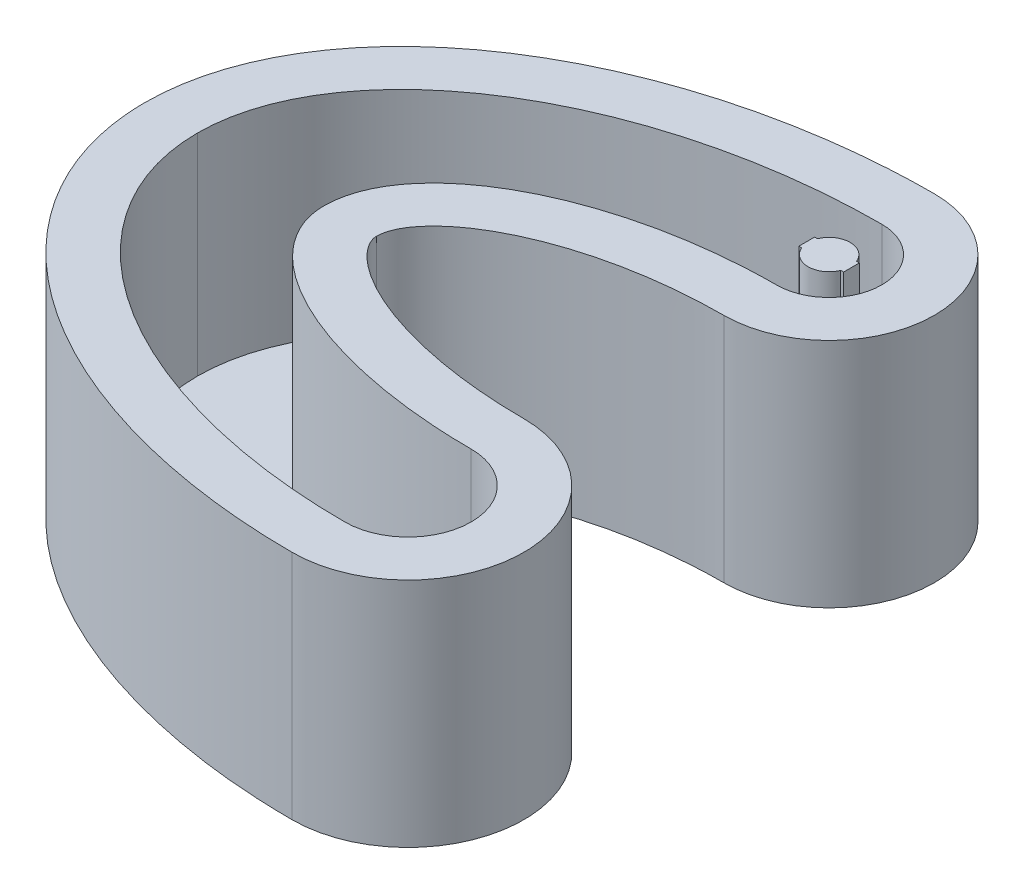
SolidWorks part; units mm, degrees
ref_plane "Front Plane" through (0, 0, 0) normal (0, 0, 1) x (1, 0, 0)
ref_plane "Top Plane" through (0, 0, 0) normal (0, 1, 0) x (1, 0, 0)
ref_plane "Right Plane" through (0, 0, 0) normal (1, 0, 0) x (0, 0, -1)
sketch "Sketch1" plane through (0, 0, 0) normal (0, 1, 0) x (1, 0, 0)
  line L0 (0, 0) -> (20, 0) construction
  line L1 (20, 0) -> (20, 25) construction
  line L2 (0, 0) -> (-20, 0) construction
  line L3 (20, 20) -> (25, 20) construction
  line L4 (17.875, 19.25) -> (22.125, 19.25)
  line L5 (17.875, 19.25) -> (17.875, 20.75)
  line L6 (17.875, 20.75) -> (22.125, 20.75)
  line L7 (22.125, 19.25) -> (22.125, 20.75)
  line L8 (17.875, 19.25) -> (22.125, 20.75) construction
  line L9 (17.875, 20.75) -> (22.125, 19.25) construction
  line L10 (25, 20) -> (25, -19) construction
  line L11 (25, -19) -> (19, -19) construction
  line L12 (19, -25) -> (19, 0) construction
  circle A2 centre (20, 20) radius 2
  arc A3 (20, 25) -> (20, 15) centre (20, 20) cw
  arc A4 (19, -25) -> (19, -13) centre (19, -19) ccw
  arc A5 (19, -35.1994) -> (19, 35.1994) centre (0, 0) ccw
  ellipse E0 centre (20, 0) end of major axis (-20, 0) minor radius 25 (-20, 0) -> (20, 25) cw
  ellipse E1 centre (20, 0) end of major axis (-8, 0) minor radius 15 (-8, 0) -> (20, 15) cw
  ellipse E2 centre (19, 0) end of major axis (46, 0) minor radius 13 (-8, 0) -> (19, -13) ccw
  ellipse E3 centre (19, 0) end of major axis (58, 0) minor radius 25 (-20, 0) -> (19, -25) ccw
  ellipse E4 centre (19, 0) end of major axis (-31, 0) minor radius 35.1994 (19, 35.1994) -> (19, -35.1994) ccw
  dimension "D3" = 5
  dimension "D7" = 4
  dimension "D9" = 39
  dimension "D11" = 6
  dimension "D13" = 80
  dimension "D1" = 20
  dimension "D2" = 25
  dimension "D4" = 20
  dimension "D5" = 12
  dimension "D6" = 4.25
  dimension "D8" = 1.5
  dimension "D10" = 6
  dimension "D12" = 19
  dimension "D14" = 50
  dimension "D15" = 35.1994
extrude "Boss-Extrude1" add sketch "Sketch1" along normal blind 20 contours A5 E4 E3 E0 A3 E1 E2 A4 | L6 L7 L4 L5 | A2
fillet "Fillet1" radius 20 2 edges at (19, 10, 35.1994) (19, 10, -35.1994)
sketch "Sketch7" plane through (0, 20, 0) normal (0, 1, 0) x (1, 0, 0)
  arc A7 (19, -30) -> (19, -8) centre (19, -19) ccw
  arc A8 (20, 10) -> (20, 30) centre (20, 20) ccw
  arc A9 (19, -30) -> (19, -8) centre (19, -19) ccw
  arc A10 (20, 10) -> (20, 30) centre (20, 20) ccw
  arc A12 (26.7157, -29.7703) -> (26.7157, 29.7703) centre (0, 0) ccw
  arc A13 (26.7157, 29.7703) -> (11.1268, 34.7603) centre (13.3579, 14.8851) ccw
  arc A14 (11.1268, -34.7603) -> (26.7157, -29.7703) centre (13.3579, -14.8851) ccw
  arc A15 (26.7157, -29.7703) -> (26.7157, 29.7703) centre (0, 0) ccw
  arc A16 (26.7157, 29.7703) -> (11.1268, 34.7603) centre (13.3579, 14.8851) ccw
  arc A17 (11.1268, -34.7603) -> (26.7157, -29.7703) centre (13.3579, -14.8851) ccw
  ellipse E6 centre (19, 0) end of major axis (-31, 0) minor radius 35.1994 (11.1268, 34.7603) -> (11.1268, -34.7603) ccw
  ellipse E7 centre (19, 0) end of major axis (-31, 0) minor radius 35.1994 (11.1268, 34.7603) -> (11.1268, -34.7603) ccw
  spline S0 degree 3 poles (2881.2153, 728.2994) (360.2182, 219.2635) (-38.0983, 72.6493) (-24.5732, -4.2682) (-24.4416, -4.8659) (-24.1276, -6.0526) (-23.9448, -6.6428) (-23.323, -8.3927) (-22.8187, -9.512) (-21.9426, -11.1279) (-21.6306, -11.656) (-20.9682, -12.692) (-20.6169, -13.2012) (-19.514, -14.6904) (-18.7208, -15.6237) (-17.0353, -17.3886) (-16.1429, -18.2201) (-14.738, -19.3991) (-14.2585, -19.7807) (-13.2784, -20.522) (-12.7764, -20.8826) (-11.2531, -21.9238) (-10.2126, -22.5659) (-7.0256, -24.356) (-4.8141, -25.3689) (-1.3874, -26.6604) (-0.2252, -27.053) (2.1282, -27.7628) (3.3107, -28.0776) (6.8745, -28.9108) (9.2719, -29.3188) (202.1373, -51.0483) (515.5099, 770.5689) (1003.1891, 2787.6642) knots -3.898537 -3.898537 -3.898537 -3.898537 0.0625 0.0625 0.09375 0.09375 0.125 0.125 0.1875 0.1875 0.21875 0.21875 0.25 0.25 0.3125 0.3125 0.375 0.375 0.40625 0.40625 0.4375 0.4375 0.5 0.5 0.625 0.625 0.6875 0.6875 0.75 0.75 0.875 0.875 10.723804 10.723804 10.723804 10.723804 only from (-25, 0) to (19, -30)
  spline S1 degree 3 poles (235.1817, -2911.03) (746.1862, 1589.4437) (242.5983, -35.9676) (10.9013, -7.3829) (8.9128, -7.0104) (5.9711, -6.2029) (4.9975, -5.8919) (3.0689, -5.1577) (2.1265, -4.7402) (0.7644, -4.0041) (0.322, -3.7419) (-0.5322, -3.1734) (-0.9444, -2.8676) (-1.7237, -2.191) (-2.0913, -1.8221) (-2.557, -1.1984) (-2.6958, -0.9817) (-2.8605, -0.6338) (-2.9082, -0.5139) (-5.5147, 8.8205) (66.4763, 33.2928) (2994.2774, -60.3933) knots -28.329853 -28.329853 -28.329853 -28.329853 0.25 0.25 0.5 0.5 0.625 0.625 0.75 0.75 0.8125 0.8125 0.875 0.875 0.9375 0.9375 0.96875 0.96875 0.984375 0.984375 2.122582 2.122582 2.122582 2.122582 only from (19, -8) to (-3, 0)
  spline S2 degree 3 poles (2931.8932, -616.5418) (131.158, -62.9524) (-7.7376, -17.3433) (-2.8149, 1.1048) (-2.7097, 1.3711) (-2.4613, 1.8742) (-2.3172, 2.1142) (-1.9996, 2.5771) (-1.8252, 2.8008) (-1.2763, 3.4396) (-0.8748, 3.8267) (-0.0246, 4.5495) (0.4268, 4.8859) (1.8219, 5.8238) (2.7986, 6.3525) (4.8131, 7.2837) (5.8526, 7.6849) (7.9772, 8.3835) (9.0481, 8.6761) (11.204, 9.1688) (12.2889, 9.3688) (229.0024, 40.9052) (685.3544, -1516.1991) (232.5259, 2926.0273) knots -2.063092 -2.063092 -2.063092 -2.063092 0.03125 0.03125 0.0625 0.0625 0.09375 0.09375 0.125 0.125 0.1875 0.1875 0.25 0.25 0.375 0.375 0.5 0.5 0.625 0.625 0.75 0.75 25.450462 25.450462 25.450462 25.450462 only from (-3, 0) to (20, 10)
  spline S3 degree 3 poles (1038.1549, -2775.3435) (507.3026, -688.6174) (197.7056, 49.7754) (10.1372, 29.3319) (7.7096, 28.9323) (4.1036, 28.118) (2.9075, 27.8105) (1.1229, 27.2911) (0.5296, 27.1083) (-0.6536, 26.7222) (-1.2446, 26.5186) (-4.1751, 25.4526) (-6.4419, 24.4488) (-9.7053, 22.677) (-10.7701, 22.0418) (-12.8476, 20.6697) (-13.8637, 19.9296) (-15.7971, 18.3618) (-16.7186, 17.532) (-18.46, 15.7697) (-19.2801, 14.8373) (-20.4214, 13.3486) (-20.7875, 12.8362) (-21.4769, 11.7945) (-21.8016, 11.2635) (-22.7132, 9.6392) (-23.238, 8.5145) (-23.8859, 6.7573) (-24.0792, 6.157) (-24.4112, 4.9479) (-24.5502, 4.3393) (-38.9862, -74.8555) (393.3239, -220.9265) (2892.8263, -679.3616) knots -9.322522 -9.322522 -9.322522 -9.322522 0.125 0.125 0.25 0.25 0.3125 0.3125 0.34375 0.34375 0.375 0.375 0.5 0.5 0.5625 0.5625 0.625 0.625 0.6875 0.6875 0.75 0.75 0.78125 0.78125 0.8125 0.8125 0.875 0.875 0.90625 0.90625 0.9375 0.9375 4.945268 4.945268 4.945268 4.945268 only from (20, 30) to (-25, 0)
  spline S4 degree 3 poles (-25, 0) (-25, -1.2403) (-24.8908, -2.462) (-24.5732, -4.2682) (-24.4416, -4.8659) (-24.1276, -6.0526) (-23.9448, -6.6428) (-23.323, -8.3927) (-22.8187, -9.512) (-21.9426, -11.1279) (-21.6306, -11.656) (-20.9682, -12.692) (-20.6169, -13.2012) (-19.514, -14.6904) (-18.7208, -15.6237) (-17.0353, -17.3886) (-16.1429, -18.2201) (-14.738, -19.3991) (-14.2585, -19.7807) (-13.2784, -20.522) (-12.7764, -20.8826) (-11.2531, -21.9238) (-10.2126, -22.5659) (-7.0256, -24.356) (-4.8141, -25.3689) (-1.3874, -26.6604) (-0.2252, -27.053) (2.1282, -27.7628) (3.3107, -28.0776) (6.8745, -28.9108) (9.2719, -29.3188) (14.1062, -29.8635) (16.5431, -30) (19, -30) knots 0 0 0 0 0.0625 0.0625 0.09375 0.09375 0.125 0.125 0.1875 0.1875 0.21875 0.21875 0.25 0.25 0.3125 0.3125 0.375 0.375 0.40625 0.40625 0.4375 0.4375 0.5 0.5 0.625 0.625 0.6875 0.6875 0.75 0.75 0.875 0.875 1 1 1 1
  spline S5 degree 3 poles (19, -8) (16.9498, -8) (14.9196, -7.8787) (10.9013, -7.3829) (8.9128, -7.0104) (5.9711, -6.2029) (4.9975, -5.8919) (3.0689, -5.1577) (2.1265, -4.7402) (0.7644, -4.0041) (0.322, -3.7419) (-0.5322, -3.1734) (-0.9444, -2.8676) (-1.7237, -2.191) (-2.0913, -1.8221) (-2.557, -1.1984) (-2.6958, -0.9817) (-2.8605, -0.6338) (-2.9082, -0.5139) (-2.9788, -0.2611) (-3, -0.1318) (-3, 0) knots 0 0 0 0 0.25 0.25 0.5 0.5 0.625 0.625 0.75 0.75 0.8125 0.8125 0.875 0.875 0.9375 0.9375 0.96875 0.96875 0.984375 0.984375 1 1 1 1
  spline S6 degree 3 poles (-3, 0) (-3, 0.285) (-2.9596, 0.5624) (-2.8149, 1.1048) (-2.7097, 1.3711) (-2.4613, 1.8742) (-2.3172, 2.1142) (-1.9996, 2.5771) (-1.8252, 2.8008) (-1.2763, 3.4396) (-0.8748, 3.8267) (-0.0246, 4.5495) (0.4268, 4.8859) (1.8219, 5.8238) (2.7986, 6.3525) (4.8131, 7.2837) (5.8526, 7.6849) (7.9772, 8.3835) (9.0481, 8.6761) (11.204, 9.1688) (12.2889, 9.3688) (15.5625, 9.8451) (17.7695, 10) (20, 10) knots 0 0 0 0 0.03125 0.03125 0.0625 0.0625 0.09375 0.09375 0.125 0.125 0.1875 0.1875 0.25 0.25 0.375 0.375 0.5 0.5 0.625 0.625 0.75 0.75 1 1 1 1
  spline S7 degree 3 poles (20, 30) (17.5069, 30) (15.0358, 29.8658) (10.1372, 29.3319) (7.7096, 28.9323) (4.1036, 28.118) (2.9075, 27.8105) (1.1229, 27.2911) (0.5296, 27.1083) (-0.6536, 26.7222) (-1.2446, 26.5186) (-4.1751, 25.4526) (-6.4419, 24.4488) (-9.7053, 22.677) (-10.7701, 22.0418) (-12.8476, 20.6697) (-13.8637, 19.9296) (-15.7971, 18.3618) (-16.7186, 17.532) (-18.46, 15.7697) (-19.2801, 14.8373) (-20.4214, 13.3486) (-20.7875, 12.8362) (-21.4769, 11.7945) (-21.8016, 11.2635) (-22.7132, 9.6392) (-23.238, 8.5145) (-23.8859, 6.7573) (-24.0792, 6.157) (-24.4112, 4.9479) (-24.5502, 4.3393) (-24.8852, 2.5011) (-25, 1.2592) (-25, 0) knots 0 0 0 0 0.125 0.125 0.25 0.25 0.3125 0.3125 0.34375 0.34375 0.375 0.375 0.5 0.5 0.5625 0.5625 0.625 0.625 0.6875 0.6875 0.75 0.75 0.78125 0.78125 0.8125 0.8125 0.875 0.875 0.90625 0.90625 0.9375 0.9375 1 1 1 1
  dimension "D1" = 5
  dimension "D2" = 0
extrude "Cut-Extrude4" cut sketch "Sketch7" against normal through all
sketch "Sketch8" plane through (0, 0, 0) normal (0, 1, 0) x (1, 0, 0)
  arc A2 (19, -30) -> (19, -8) centre (19, -19) ccw
  arc A3 (20, 10) -> (20, 30) centre (20, 20) ccw
  arc A4 (19, -30) -> (19, -8) centre (19, -19) ccw
  arc A5 (20, 10) -> (20, 30) centre (20, 20) ccw
  spline S4 degree 3 poles (1277.6418, -3746.2183) (597.6218, -913.316) (223.9597, 52.6368) (10.1372, 29.3319) (7.7096, 28.9323) (4.1036, 28.118) (2.9075, 27.8105) (1.1229, 27.2911) (0.5296, 27.1083) (-0.6536, 26.7222) (-1.2446, 26.5186) (-4.1751, 25.4526) (-6.4419, 24.4488) (-9.7053, 22.677) (-10.7701, 22.0418) (-12.8476, 20.6697) (-13.8637, 19.9296) (-15.7971, 18.3618) (-16.7186, 17.532) (-18.46, 15.7697) (-19.2801, 14.8373) (-20.4214, 13.3486) (-20.7875, 12.8362) (-21.4769, 11.7945) (-21.8016, 11.2635) (-22.7132, 9.6392) (-23.238, 8.5145) (-23.8859, 6.7573) (-24.0792, 6.157) (-24.4112, 4.9479) (-24.5502, 4.3393) (-40.6927, -84.2171) (502.6662, -256.6876) (3876.8887, -856.9172) knots -10.662391 -10.662391 -10.662391 -10.662391 0.125 0.125 0.25 0.25 0.3125 0.3125 0.34375 0.34375 0.375 0.375 0.5 0.5 0.5625 0.5625 0.625 0.625 0.6875 0.6875 0.75 0.75 0.78125 0.78125 0.8125 0.8125 0.875 0.875 0.90625 0.90625 0.9375 0.9375 5.422719 5.422719 5.422719 5.422719 only from (20, 30) to (-25, 0)
  spline S5 degree 3 poles (3861.8065, 923.4643) (459.629, 254.7306) (-39.6769, 81.6267) (-24.5732, -4.2682) (-24.4416, -4.8659) (-24.1276, -6.0526) (-23.9448, -6.6428) (-23.323, -8.3927) (-22.8187, -9.512) (-21.9426, -11.1279) (-21.6306, -11.656) (-20.9682, -12.692) (-20.6169, -13.2012) (-19.514, -14.6904) (-18.7208, -15.6237) (-17.0353, -17.3886) (-16.1429, -18.2201) (-14.738, -19.3991) (-14.2585, -19.7807) (-13.2784, -20.522) (-12.7764, -20.8826) (-11.2531, -21.9238) (-10.2126, -22.5659) (-7.0256, -24.356) (-4.8141, -25.3689) (-1.3874, -26.6604) (-0.2252, -27.053) (2.1282, -27.7628) (3.3107, -28.0776) (6.8745, -28.9108) (9.2719, -29.3188) (230.281, -54.2192) (610.8122, 1031.8104) (1230.9762, 3761.3561) knots -4.3645 -4.3645 -4.3645 -4.3645 0.0625 0.0625 0.09375 0.09375 0.125 0.125 0.1875 0.1875 0.21875 0.21875 0.25 0.25 0.3125 0.3125 0.375 0.375 0.40625 0.40625 0.4375 0.4375 0.5 0.5 0.625 0.625 0.6875 0.6875 0.75 0.75 0.875 0.875 12.179221 12.179221 12.179221 12.179221 only from (-25, 0) to (19, -30)
  spline S6 degree 3 poles (117.9763, -3904.0932) (815.1323, 1815.457) (258.0393, -37.8725) (10.9013, -7.3829) (8.9128, -7.0104) (5.9711, -6.2029) (4.9975, -5.8919) (3.0689, -5.1577) (2.1265, -4.7402) (0.7644, -4.0041) (0.322, -3.7419) (-0.5322, -3.1734) (-0.9444, -2.8676) (-1.7237, -2.191) (-2.0913, -1.8221) (-2.557, -1.1984) (-2.6958, -0.9817) (-2.8605, -0.6338) (-2.9082, -0.5139) (-5.7794, 9.7684) (82.0888, 38.4932) (3992.3166, -93.2291) knots -30.251159 -30.251159 -30.251159 -30.251159 0.25 0.25 0.5 0.5 0.625 0.625 0.75 0.75 0.8125 0.8125 0.875 0.875 0.9375 0.9375 0.96875 0.96875 0.984375 0.984375 2.239755 2.239755 2.239755 2.239755 only from (19, -8) to (-3, 0)
  spline S7 degree 3 poles (3912.815, -809.7999) (162.1452, -72.9066) (-8.2506, -19.2657) (-2.8149, 1.1048) (-2.7097, 1.3711) (-2.4613, 1.8742) (-2.3172, 2.1142) (-1.9996, 2.5771) (-1.8252, 2.8008) (-1.2763, 3.4396) (-0.8748, 3.8267) (-0.0246, 4.5495) (0.4268, 4.8859) (1.8219, 5.8238) (2.7986, 6.3525) (4.8131, 7.2837) (5.8526, 7.6849) (7.9772, 8.3835) (9.0481, 8.6761) (11.204, 9.1688) (12.2889, 9.3688) (243.6985, 43.0438) (748.6795, -1735.8324) (126.9016, 3920.3394) knots -2.284591 -2.284591 -2.284591 -2.284591 0.03125 0.03125 0.0625 0.0625 0.09375 0.09375 0.125 0.125 0.1875 0.1875 0.25 0.25 0.375 0.375 0.5 0.5 0.625 0.625 0.75 0.75 27.133965 27.133965 27.133965 27.133965 only from (-3, 0) to (20, 10)
  spline S8 degree 3 poles (20, 30) (17.5069, 30) (15.0358, 29.8658) (10.1372, 29.3319) (7.7096, 28.9323) (4.1036, 28.118) (2.9075, 27.8105) (1.1229, 27.2911) (0.5296, 27.1083) (-0.6536, 26.7222) (-1.2446, 26.5186) (-4.1751, 25.4526) (-6.4419, 24.4488) (-9.7053, 22.677) (-10.7701, 22.0418) (-12.8476, 20.6697) (-13.8637, 19.9296) (-15.7971, 18.3618) (-16.7186, 17.532) (-18.46, 15.7697) (-19.2801, 14.8373) (-20.4214, 13.3486) (-20.7875, 12.8362) (-21.4769, 11.7945) (-21.8016, 11.2635) (-22.7132, 9.6392) (-23.238, 8.5145) (-23.8859, 6.7573) (-24.0792, 6.157) (-24.4112, 4.9479) (-24.5502, 4.3393) (-24.8852, 2.5011) (-25, 1.2592) (-25, 0) knots 0 0 0 0 0.125 0.125 0.25 0.25 0.3125 0.3125 0.34375 0.34375 0.375 0.375 0.5 0.5 0.5625 0.5625 0.625 0.625 0.6875 0.6875 0.75 0.75 0.78125 0.78125 0.8125 0.8125 0.875 0.875 0.90625 0.90625 0.9375 0.9375 1 1 1 1
  spline S9 degree 3 poles (-25, 0) (-25, -1.2403) (-24.8908, -2.462) (-24.5732, -4.2682) (-24.4416, -4.8659) (-24.1276, -6.0526) (-23.9448, -6.6428) (-23.323, -8.3927) (-22.8187, -9.512) (-21.9426, -11.1279) (-21.6306, -11.656) (-20.9682, -12.692) (-20.6169, -13.2012) (-19.514, -14.6904) (-18.7208, -15.6237) (-17.0353, -17.3886) (-16.1429, -18.2201) (-14.738, -19.3991) (-14.2585, -19.7807) (-13.2784, -20.522) (-12.7764, -20.8826) (-11.2531, -21.9238) (-10.2126, -22.5659) (-7.0256, -24.356) (-4.8141, -25.3689) (-1.3874, -26.6604) (-0.2252, -27.053) (2.1282, -27.7628) (3.3107, -28.0776) (6.8745, -28.9108) (9.2719, -29.3188) (14.1062, -29.8635) (16.5431, -30) (19, -30) knots 0 0 0 0 0.0625 0.0625 0.09375 0.09375 0.125 0.125 0.1875 0.1875 0.21875 0.21875 0.25 0.25 0.3125 0.3125 0.375 0.375 0.40625 0.40625 0.4375 0.4375 0.5 0.5 0.625 0.625 0.6875 0.6875 0.75 0.75 0.875 0.875 1 1 1 1
  spline S10 degree 3 poles (19, -8) (16.9498, -8) (14.9196, -7.8787) (10.9013, -7.3829) (8.9128, -7.0104) (5.9711, -6.2029) (4.9975, -5.8919) (3.0689, -5.1577) (2.1265, -4.7402) (0.7644, -4.0041) (0.322, -3.7419) (-0.5322, -3.1734) (-0.9444, -2.8676) (-1.7237, -2.191) (-2.0913, -1.8221) (-2.557, -1.1984) (-2.6958, -0.9817) (-2.8605, -0.6338) (-2.9082, -0.5139) (-2.9788, -0.2611) (-3, -0.1318) (-3, 0) knots 0 0 0 0 0.25 0.25 0.5 0.5 0.625 0.625 0.75 0.75 0.8125 0.8125 0.875 0.875 0.9375 0.9375 0.96875 0.96875 0.984375 0.984375 1 1 1 1
  spline S11 degree 3 poles (-3, 0) (-3, 0.285) (-2.9596, 0.5624) (-2.8149, 1.1048) (-2.7097, 1.3711) (-2.4613, 1.8742) (-2.3172, 2.1142) (-1.9996, 2.5771) (-1.8252, 2.8008) (-1.2763, 3.4396) (-0.8748, 3.8267) (-0.0246, 4.5495) (0.4268, 4.8859) (1.8219, 5.8238) (2.7986, 6.3525) (4.8131, 7.2837) (5.8526, 7.6849) (7.9772, 8.3835) (9.0481, 8.6761) (11.204, 9.1688) (12.2889, 9.3688) (15.5625, 9.8451) (17.7695, 10) (20, 10) knots 0 0 0 0 0.03125 0.03125 0.0625 0.0625 0.09375 0.09375 0.125 0.125 0.1875 0.1875 0.25 0.25 0.375 0.375 0.5 0.5 0.625 0.625 0.75 0.75 1 1 1 1
  dimension "D1" = 0
extrude "Boss-Extrude3" add sketch "Sketch8" against normal blind 2
